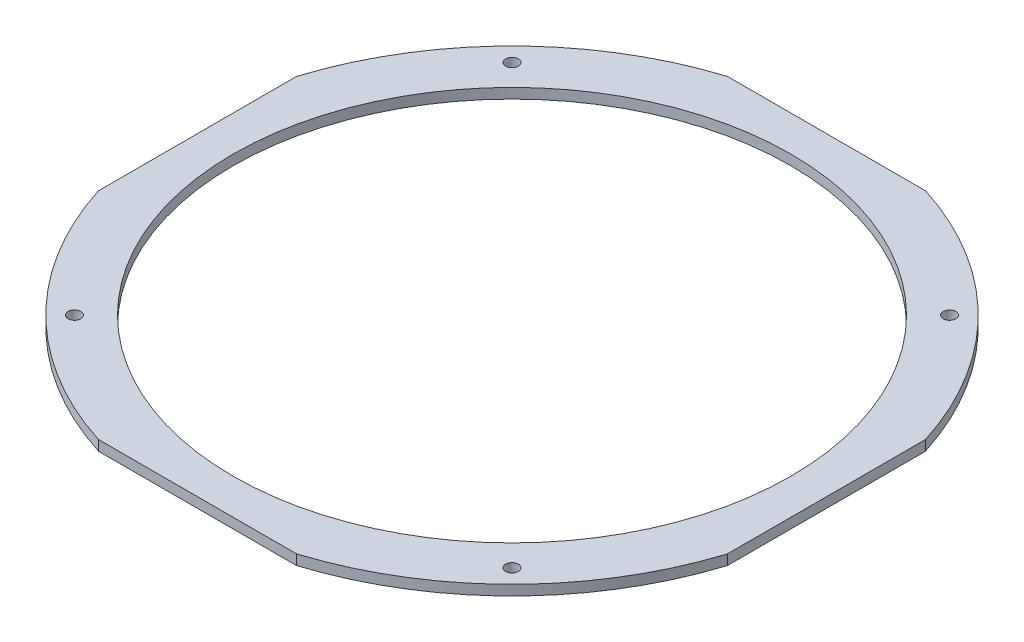
SolidWorks part; units mm, degrees
material "Thornel Mat VMA"
ref_plane "前视基准面" through (0, 0, 0) normal (0, 0, 1) x (1, 0, 0)
ref_plane "上视基准面" through (0, 0, 0) normal (0, 1, 0) x (1, 0, 0)
ref_plane "右视基准面" through (0, 0, 0) normal (1, 0, 0) x (0, 0, -1)
sketch "草图1" plane through (0, 0, 0) normal (0, 1, 0) x (1, 0, 0)
  circle A0 centre (0, 0) radius 65
  circle A1 centre (0, 0) radius 55
  dimension "D1" = 130
  dimension "D2" = 110
extrude "凸台-拉伸1" add sketch "草图1" along normal blind 2
sketch "草图3" plane through (0, 2, 0) normal (0, 1, 0) x (1, 0, 0)
  line L1 (-62, 62) -> (62, 62)
  line L2 (-62, 62) -> (-62, -62)
  line L3 (-62, -62) -> (62, -62)
  line L4 (62, 62) -> (62, -62)
  line L5 (0, -62) -> (0, 62) construction
  line L6 (-62, 0) -> (62, 0) construction
  line L7 (-84.4888, 72.3797) -> (84.4888, 72.3797)
  line L8 (-84.4888, 72.3797) -> (-84.4888, -72.3797)
  line L9 (-84.4888, -72.3797) -> (84.4888, -72.3797)
  line L10 (84.4888, 72.3797) -> (84.4888, -72.3797)
  line L11 (0, -72.3797) -> (0, 72.3797) construction
  line L12 (-84.4888, 0) -> (84.4888, 0) construction
  point P0 (0, 0)
  point P4 (0, 0)
  dimension "D1" = 124
  dimension "D2" = 124
extrude "切除-拉伸1" cut sketch "草图3" against normal blind 3
sketch "草图4" plane through (0, 2, 0) normal (0, 1, 0) x (1, 0, 0)
  line L0 (-103.8977, 0) -> (86.028, 0) construction
  line L1 (0, 77.2995) -> (0, -80.1518) construction
  line L2 (0, 0) -> (59.2262, -59.2262) construction
  circle A0 centre (0, 0) radius 61 construction
  circle A2 centre (43.1335, -43.1335) radius 1.25
  circle A3 centre (-43.1335, -43.1335) radius 1.25
  circle A4 centre (-43.1335, 43.1335) radius 1.25
  circle A5 centre (43.1335, 43.1335) radius 1.25
  dimension "D1" = 122
  dimension "D2" = 2.5
  dimension "D3" = 61
  dimension "D4" = 4
extrude "切除-拉伸2" cut sketch "草图4" against normal blind 3
